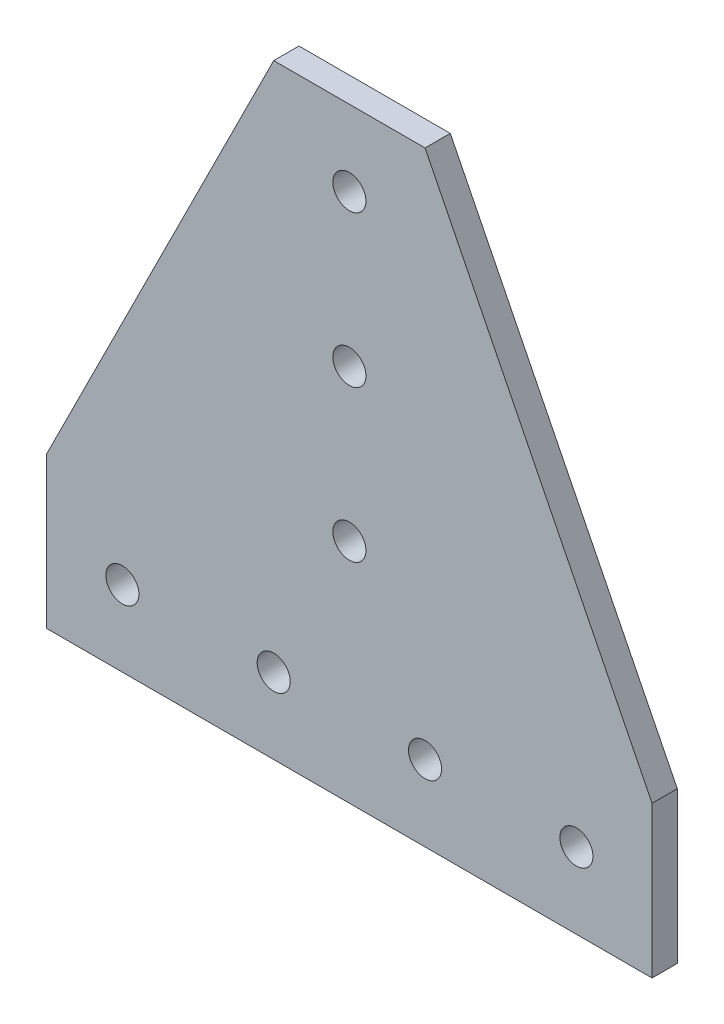
SolidWorks part; units mm, degrees
ref_plane "Front Plane" through (0, 0, 0) normal (0, 0, 1) x (1, 0, 0)
ref_plane "Top Plane" through (0, 0, 0) normal (0, 1, 0) x (1, 0, 0)
ref_plane "Right Plane" through (0, 0, 0) normal (1, 0, 0) x (0, 0, -1)
sketch "Sketch1" plane through (0, 0, 0) normal (0, 0, 1) x (1, 0, 0)
  line L0 (0, 0) -> (0, 38.1)
  line L4 (152.4, 38.1) -> (95.25, 152.4)
  line L5 (152.4, 0) -> (0, 0)
  line L7 (152.4, 38.1) -> (152.4, 0)
  line L8 (57.15, 152.4) -> (95.25, 152.4)
  line L9 (0, 38.1) -> (57.15, 152.4)
  circle A0 centre (19.05, 19.05) radius 4.1656
  circle A1 centre (57.15, 19.05) radius 4.1656
  circle A2 centre (95.25, 19.05) radius 4.1656
  circle A3 centre (133.35, 19.05) radius 4.1656
  circle A4 centre (76.2, 133.35) radius 4.1656
  circle A5 centre (76.2, 95.25) radius 4.1656
  circle A6 centre (76.2, 57.15) radius 4.1656
  dimension "D1" = 19.05
  dimension "D2" = 19.05
  dimension "D5" = 19.05
  dimension "D3" = 4
  dimension "B1" = 152.4
  dimension "D4" = 57.15
  dimension "C1" = 38.1
  dimension "C2" = 38.1
  dimension "B2" = 152.4
  dimension "D6" = 19.05
  dimension "D7" = 3
extrude "Boss-Extrude2" add sketch "Sketch1" along normal blind 6.35
